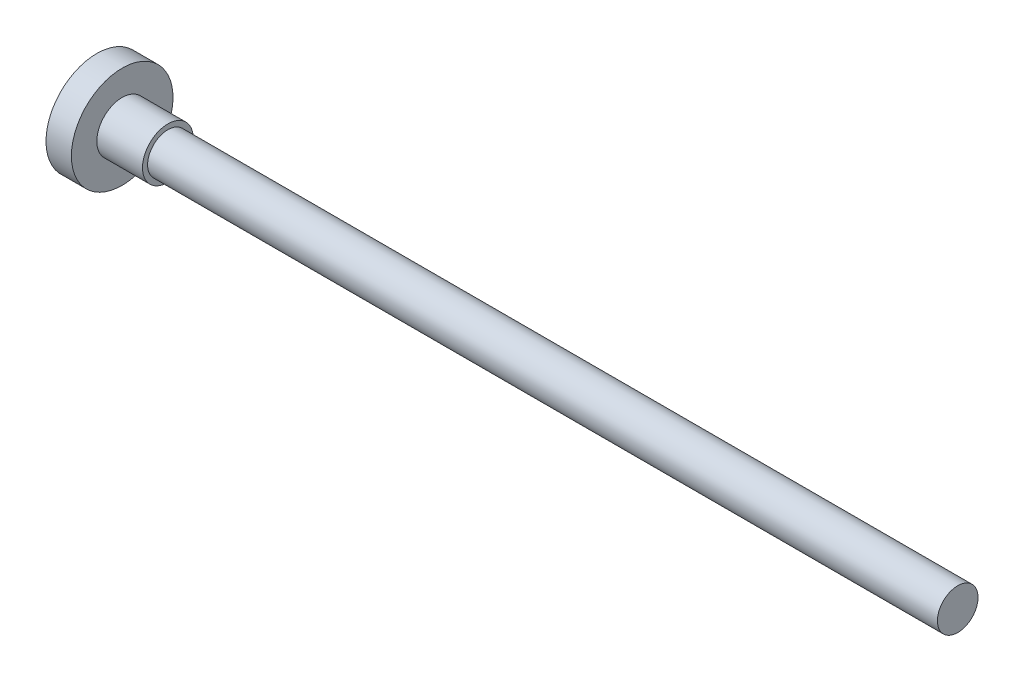
SolidWorks part; units mm, degrees
ref_plane "前视基准面" through (0, 0, 0) normal (0, 0, 1) x (1, 0, 0)
ref_plane "上视基准面" through (0, 0, 0) normal (0, 1, 0) x (1, 0, 0)
ref_plane "右视基准面" through (0, 0, 0) normal (1, 0, 0) x (0, 0, -1)
sketch "草图1" plane through (0, 0, 0) normal (0, 1, 0) x (1, 0, 0)
  line L0 (-88.4158, 0) -> (47.6608, 0) construction
  line L1 (0, 69.2371) -> (0, -43.4285) construction
  line L2 (0, 0) -> (0, 10)
  line L3 (0, 10) -> (5, 10)
  line L4 (5, 10) -> (5, 5)
  line L5 (5, 5) -> (14, 5)
  line L6 (14, 5) -> (14, 4)
  line L7 (14, 4) -> (169.5, 4)
  line L8 (169.5, 4) -> (169.5, 0)
  line L9 (0, 0) -> (169.5, 0)
revolve "旋转1" add sketch "草图1" angle 360 about L0
